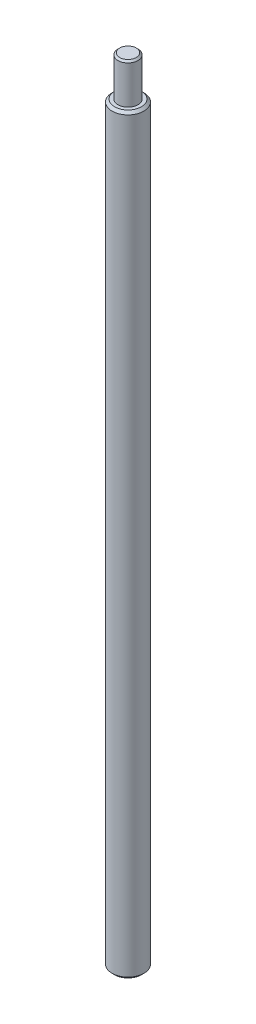
SolidWorks part; units mm, degrees
material "STAINLESS STEEL, 304"
ref_plane "Front Plane" through (0, 0, 0) normal (0, 0, 1) x (1, 0, 0)
ref_plane "Top Plane" through (0, 0, 0) normal (0, 1, 0) x (1, 0, 0)
ref_plane "Right Plane" through (0, 0, 0) normal (1, 0, 0) x (0, 0, -1)
sketch "Sketch6" plane through (0, 0, 0) normal (0, 1, 0) x (1, 0, 0)
  circle A0 centre (0, 0) radius 3.175
  dimension "D1" = 6.35
extrude "Boss-Extrude4" add sketch "Sketch6" along normal blind 150 separate body
sketch "Sketch7" plane through (0, 150, 0) normal (0, 1, 0) x (-1, 0, 0)
  circle A0 centre (0, 0) radius 2
  dimension "D1" = 4
extrude "Boss-Extrude5" add sketch "Sketch7" along normal blind 8
cosmetic thread "Cosmetic Thread1" parameters "D2"=3.22
chamfer "Chamfer1" distance 0.5 angle 45 2 edges at (0, 0, 3.175) (0, 150, 3.175)
chamfer "Chamfer2" distance 0.35 angle 45 1 edges at (0, 158, 2)
